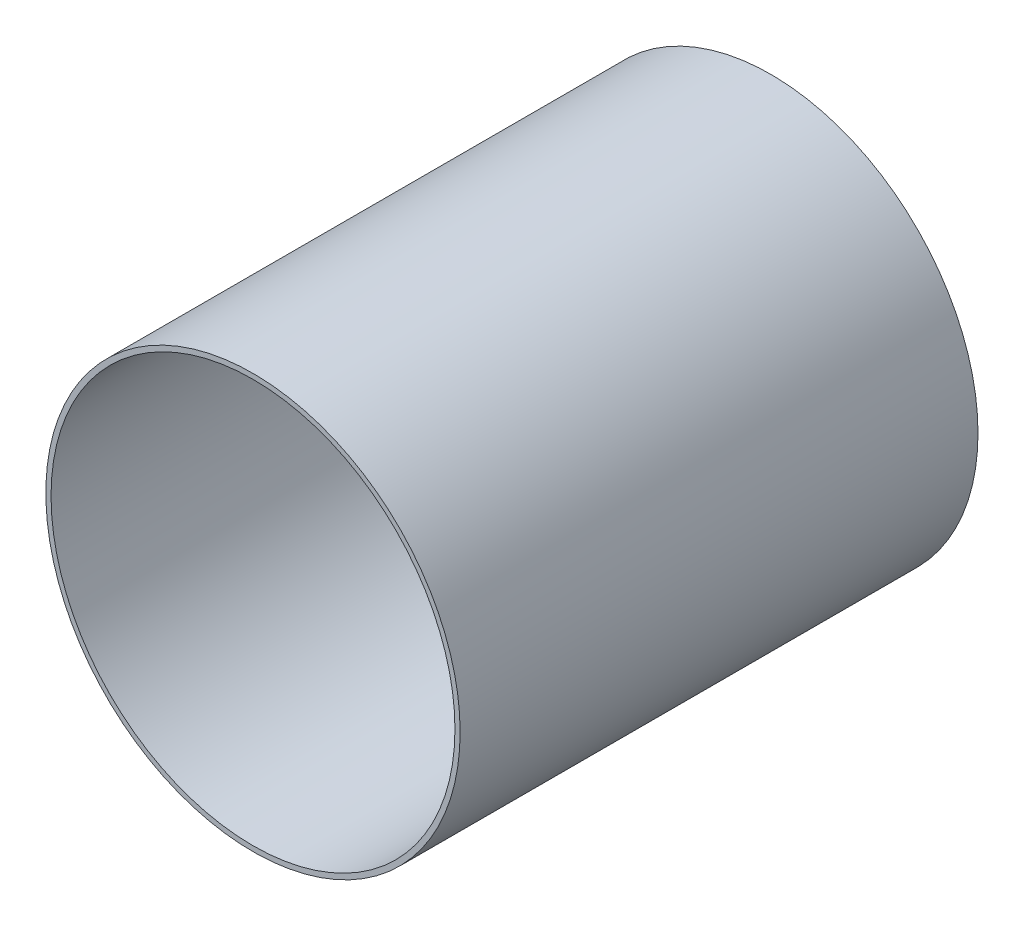
SolidWorks part; units mm, degrees
ref_plane "Front Plane" through (0, 0, 0) normal (0, 0, 1) x (1, 0, 0)
ref_plane "Top Plane" through (0, 0, 0) normal (0, 1, 0) x (1, 0, 0)
ref_plane "Right Plane" through (0, 0, 0) normal (1, 0, 0) x (0, 0, -1)
sketch "Sketch1" plane through (0, 0, 0) normal (0, 0, 1) x (1, 0, 0)
  circle A0 centre (0, 0) radius 101.6
  dimension "D1" = 203.2
extrude "Boss-Extrude1" add sketch "Sketch1" along normal blind 254
shell "Shell1" thickness 2.54
sketch "Sketch2" plane through (0, 0, 2.54) normal (0, 0, 1) x (1, 0, 0)
  circle A0 centre (0, 0) radius 12.7
  dimension "D1" = 25.4
extrude "Cut-Extrude1" cut sketch "Sketch2" against normal blind 254
